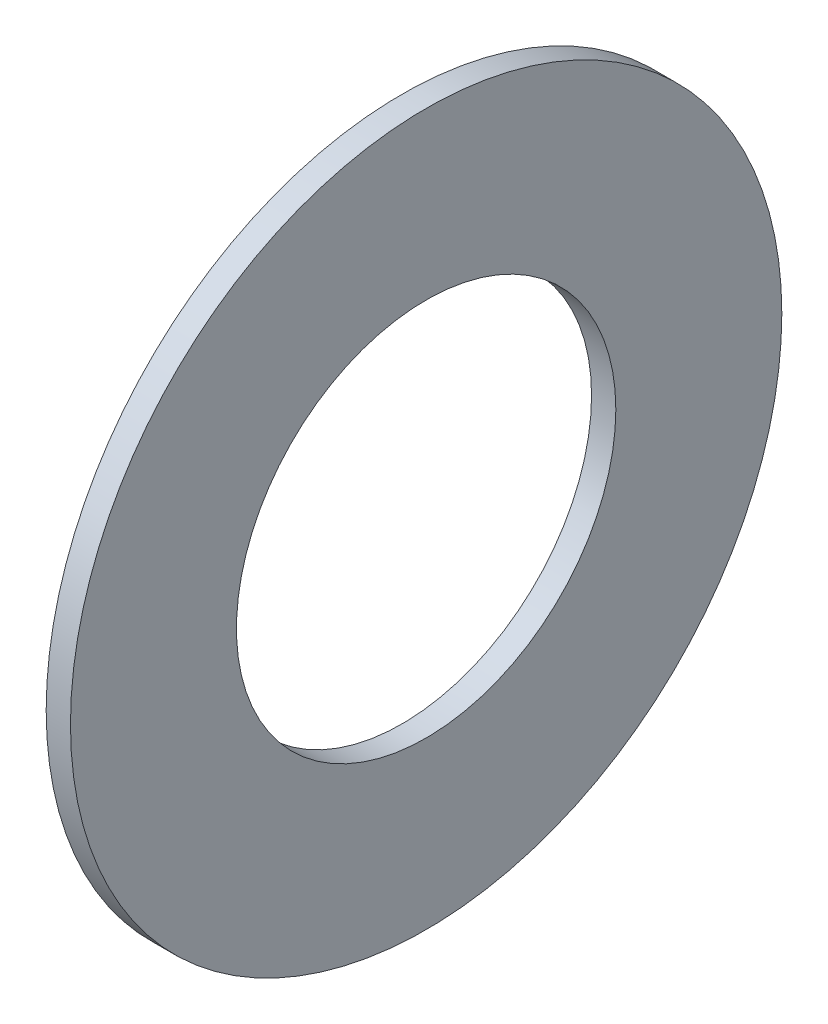
SolidWorks part; units mm, degrees
ref_plane "Front Plane" through (0, 0, 0) normal (0, 0, 1) x (1, 0, 0)
ref_plane "Top Plane" through (0, 0, 0) normal (0, 1, 0) x (1, 0, 0)
ref_plane "Right Plane" through (0, 0, 0) normal (1, 0, 0) x (0, 0, -1)
sketch "Sketch1" plane through (0, 0, 0) normal (1, 0, 0) x (0, 0, -1)
  circle A0 centre (0, 0) radius 11.9062
  circle A1 centre (0, 0) radius 6.35
  dimension "OD" = 23.8125
  dimension "Shaft Dia" = 12.7
extrude "Extrude1" add sketch "Sketch1" along normal blind 0.8128
